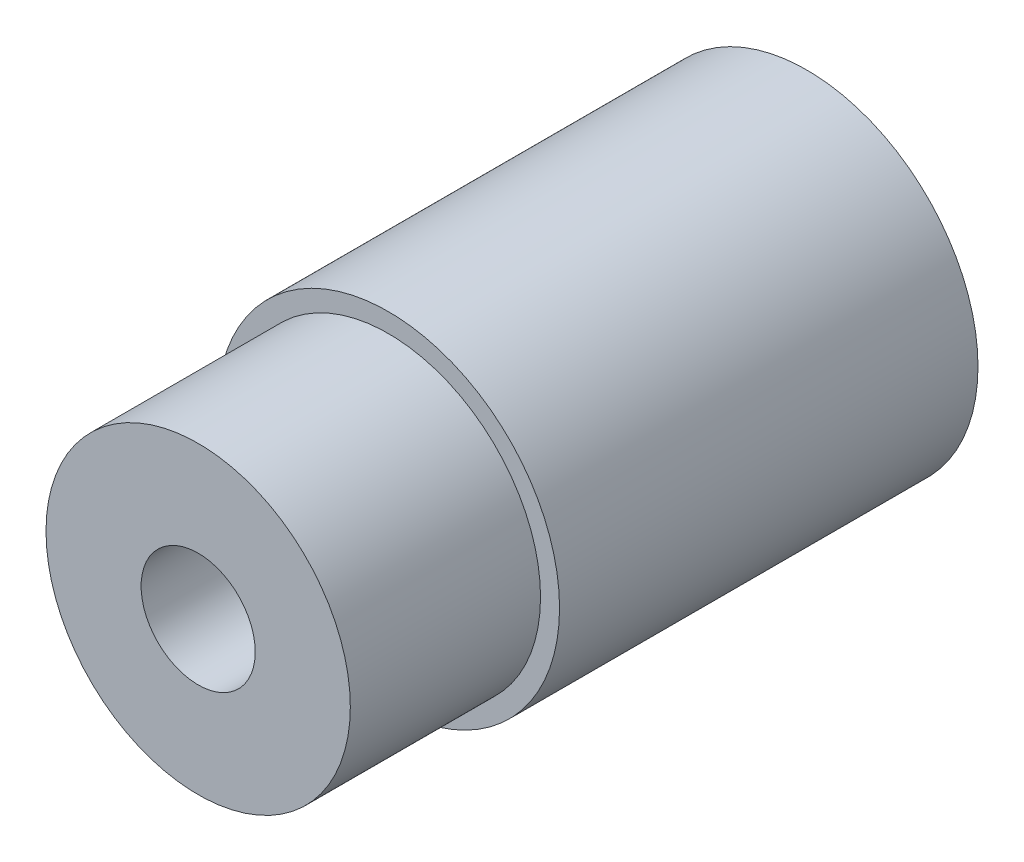
SolidWorks part; units mm, degrees
ref_plane "前视基准面" through (0, 0, 0) normal (0, 0, 1) x (1, 0, 0)
ref_plane "上视基准面" through (0, 0, 0) normal (0, 1, 0) x (1, 0, 0)
ref_plane "右视基准面" through (0, 0, 0) normal (1, 0, 0) x (0, 0, -1)
other "Configuration Table"
sketch "草图1" plane through (0, 0, 0) normal (0, 0, 1) x (1, 0, 0)
  circle A0 centre (0, 0) radius 8
  dimension "D1" = 16
extrude "凸台-拉伸1" add sketch "草图1" along normal blind 32
sketch "草图2" plane through (0, 0, 0) normal (0, 0, -1) x (-1, 0, 0)
  circle A0 centre (0, 0) radius 9
  dimension "D1" = 18
extrude "凸台-拉伸2" add sketch "草图2" against normal blind 22
sketch "草图3" plane through (0, 0, 32) normal (0, 0, 1) x (1, 0, 0)
  circle A0 centre (0, 0) radius 3
  dimension "D1" = 6
extrude "切除-拉伸1" cut sketch "草图3" against normal up to next
